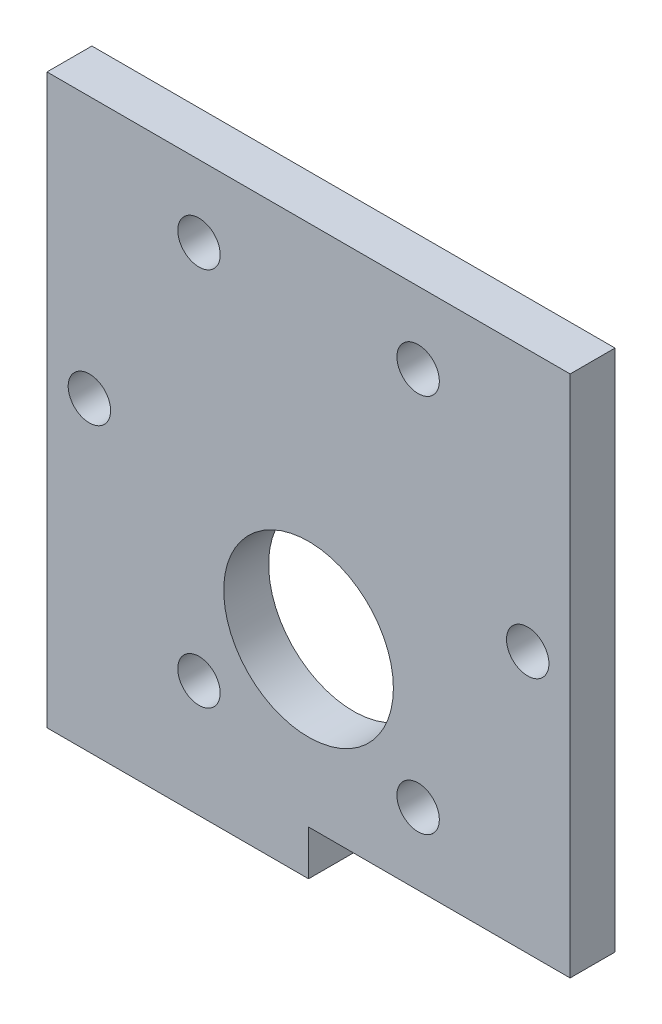
SolidWorks part; units mm, degrees
ref_plane "Front Plane" through (0, 0, 0) normal (0, 0, 1) x (1, 0, 0)
ref_plane "Top Plane" through (0, 0, 0) normal (0, 1, 0) x (1, 0, 0)
ref_plane "Right Plane" through (0, 0, 0) normal (1, 0, 0) x (0, 0, -1)
sketch "Sketch1" plane through (0, 0, 0) normal (0, 0, 1) x (1, 0, 0)
  line L0 (18.5, 0) -> (18.5, -3.175)
  line L1 (18.5, 0) -> (37, 0)
  line L2 (0, 0) -> (0, 37)
  line L3 (0, 37) -> (37, 37)
  line L4 (37, 0) -> (37, 37)
  line L5 (18.5, -3.175) -> (0, -3.175)
  line L6 (0, -3.175) -> (0, 0)
  line L7 (18.5, 0) -> (0, 0) construction
  line L8 (18.5, 0) -> (18.5, 11.35) construction
  line L10 (37, 0) -> (0, 37) construction
  circle A1 centre (18.5, 11.5) radius 6 construction
  circle A2 centre (18.5, 11.5) radius 6
  circle A3 centre (34, 18.5) radius 1.5 construction
  circle A4 centre (34, 18.5) radius 1.5
  circle A5 centre (26.25, 5.0766) radius 1.5 construction
  circle A6 centre (26.25, 5.0766) radius 1.5
  circle A7 centre (10.75, 5.0766) radius 1.5 construction
  circle A8 centre (10.75, 5.0766) radius 1.5
  circle A9 centre (3, 18.5) radius 1.5 construction
  circle A10 centre (3, 18.5) radius 1.5
  circle A11 centre (10.75, 31.9234) radius 1.5 construction
  circle A12 centre (10.75, 31.9234) radius 1.5
  circle A13 centre (26.25, 31.9234) radius 1.5 construction
  circle A14 centre (26.25, 31.9234) radius 1.5
  point P9 (0, 0)
  point P10 (0, 0)
  dimension "D1" = 37
  dimension "D2" = 37
  dimension "D3" = 3.175
extrude "Boss-Extrude1" add sketch "Sketch1" along normal blind 3.175
